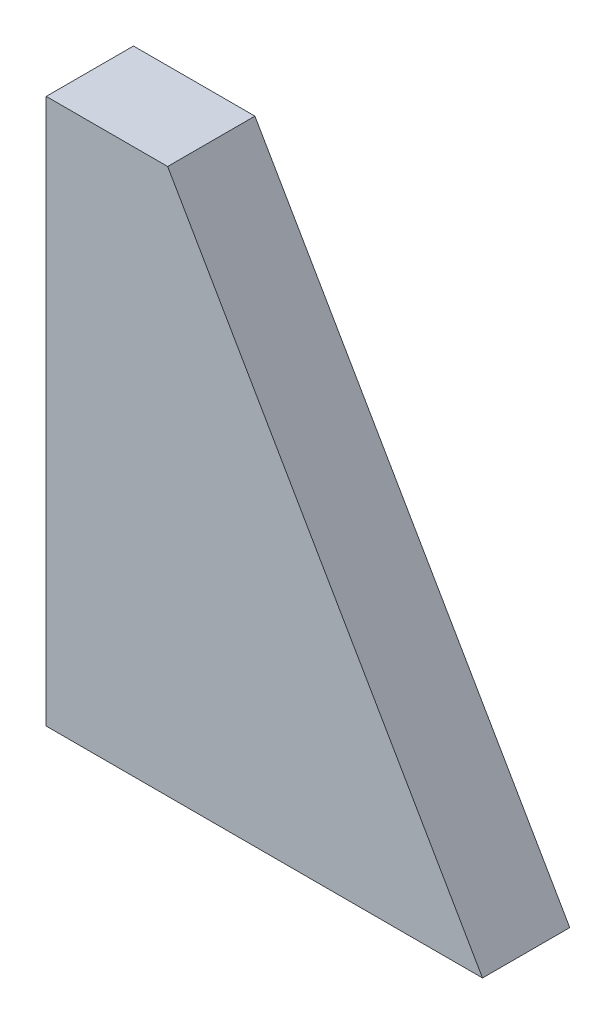
SolidWorks part; units mm, degrees
ref_plane "Front" through (0, 0, 0) normal (0, 0, 1) x (1, 0, 0)
ref_plane "Top" through (0, 0, 0) normal (0, 1, 0) x (1, 0, 0)
ref_plane "Right" through (0, 0, 0) normal (1, 0, 0) x (0, 0, -1)
sketch "Sketch1" plane through (0, 0, 0) normal (0, 0, 1) x (1, 0, 0)
  line L0 (20, -25) -> (-8.8675, 25)
  line L1 (-20, -25) -> (20, -25)
  line L2 (-20, -25) -> (-20, 25)
  line L3 (-20, 25) -> (20, 25)
  line L4 (20, -25) -> (20, 25)
  line L5 (-20, -25) -> (20, 25) construction
  line L6 (-20, 25) -> (20, -25) construction
  point P0 (0, 0)
  dimension "D1" = 40
  dimension "D2" = 50
  dimension "D3" = 60
extrude "Boss-Extrude1" add sketch "Sketch1" along normal blind 8 contours L3 L2 L1 L0
